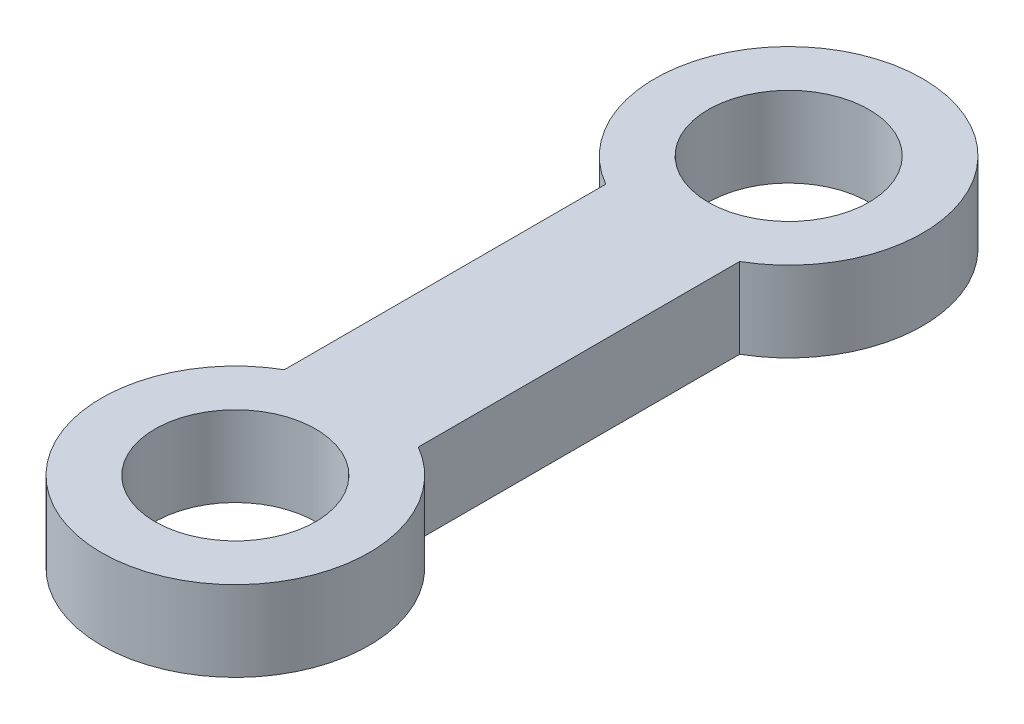
SolidWorks part; units mm, degrees
ref_plane "前视基准面" through (0, 0, 0) normal (0, 0, 1) x (1, 0, 0)
ref_plane "上视基准面" through (0, 0, 0) normal (0, 1, 0) x (1, 0, 0)
ref_plane "右视基准面" through (0, 0, 0) normal (1, 0, 0) x (0, 0, -1)
other "Configuration Table"
sketch "草图2" plane through (0, 0, 0) normal (0, 1, 0) x (1, 0, 0)
  line L15 (-2.5, -4.3301) -> (2.5, -4.3301)
  line L16 (-2.5, -4.3301) -> (-2.5, -16.3301)
  line L17 (-2.5, -16.3301) -> (2.5, -16.3301)
  line L18 (2.5, -4.3301) -> (2.5, -16.3301)
  circle A14 centre (0, 0) radius 3
  circle A15 centre (0, 0) radius 5
  circle A16 centre (0, -20.6603) radius 3
  circle A17 centre (0, -20.6603) radius 5
  dimension "D1" = 6
  dimension "D2" = 2
  dimension "D3" = 5
  dimension "D4" = 12
extrude "凸台-拉伸1" add sketch "草图2" along normal blind 3 contours L15 A15 A14 | L17 A17 A16
